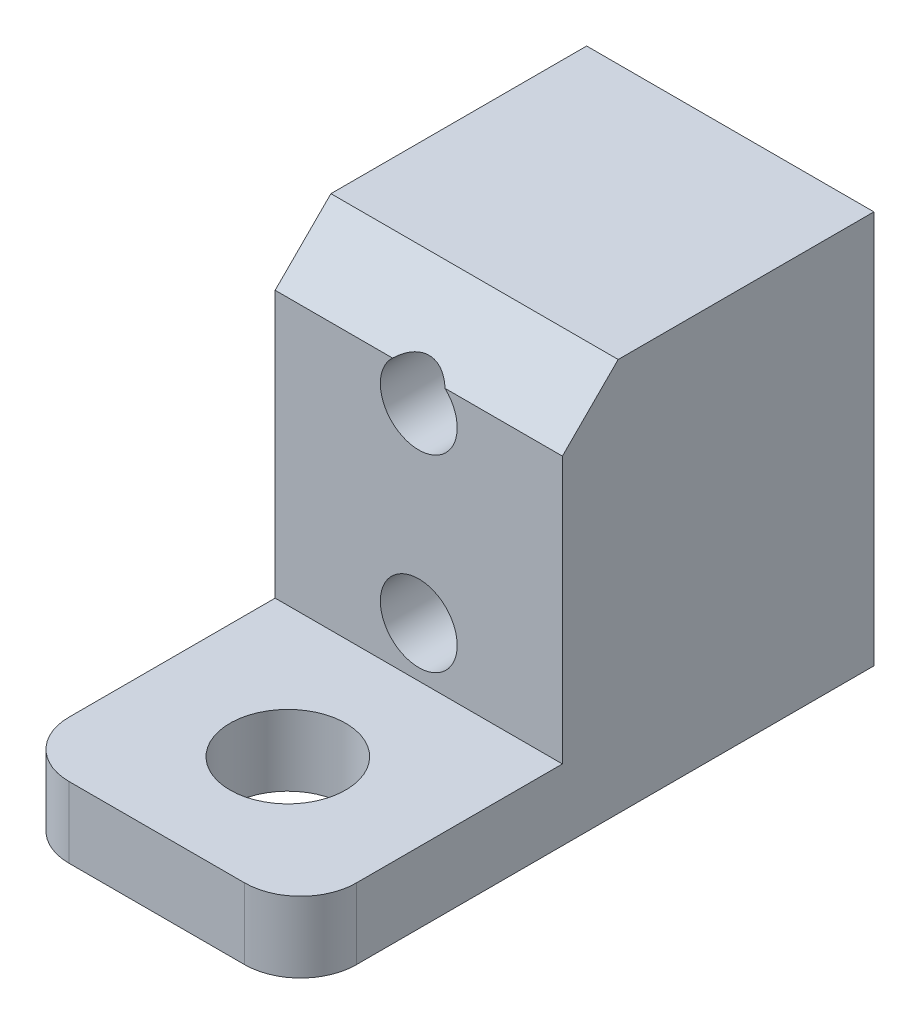
SolidWorks part; units mm, degrees
ref_plane "Front Plane" through (0, 0, 0) normal (0, 0, 1) x (1, 0, 0)
ref_plane "Top Plane" through (0, 0, 0) normal (0, 1, 0) x (1, 0, 0)
ref_plane "Right Plane" through (0, 0, 0) normal (1, 0, 0) x (0, 0, -1)
sketch "Sketch1" plane through (0, 0, 0) normal (0, 0, 1) x (1, 0, 0)
  line L1 (-6.5405, -8.9535) -> (6.5405, -8.9535)
  line L2 (-6.5405, -8.9535) -> (-6.5405, 8.9535)
  line L3 (-6.5405, 8.9535) -> (6.5405, 8.9535)
  line L4 (6.5405, -8.9535) -> (6.5405, 8.9535)
  line L5 (-6.5405, -8.9535) -> (6.5405, 8.9535) construction
  line L6 (-6.5405, 8.9535) -> (6.5405, -8.9535) construction
  point P0 (0, 0)
  dimension "D1" = 17.907
  dimension "D2" = 13.081
extrude "Boss-Extrude1" add sketch "Sketch1" along normal blind 14.1859
sketch "Sketch2" plane through (0, 0, 14.1859) normal (0, 0, 1) x (1, 0, 0)
  line L0 (6.5405, -8.9535) -> (6.5405, 8.9535) construction
  line L1 (-6.5405, -8.9535) -> (6.5405, -8.9535)
  line L2 (-6.5405, -8.9535) -> (-6.5405, -5.7277)
  line L3 (-6.5405, -5.7277) -> (6.5405, -5.7277)
  line L4 (6.5405, -8.9535) -> (6.5405, -5.7277)
  dimension "D1" = 3.2258
extrude "Boss-Extrude2" add sketch "Sketch2" along normal blind 11.9253
chamfer "Chamfer1" distance 2.54 angle 45 1 edges at (0, 8.9535, 14.1859)
fillet "Fillet1" radius 2.54 2 edges at (6.5405, -7.3406, 26.1112) (-6.5405, -7.3406, 26.1112)
sketch "Sketch3" plane through (0, -5.7277, 0) normal (0, 1, 0) x (1, 0, 0)
  line L0 (0, -26.1112) -> (0, -14.1859) construction
  line L2 (4.0005, -26.1112) -> (-4.0005, -26.1112) construction
  line L4 (6.5405, -14.1859) -> (-6.5405, -14.1859) construction
  line L5 (0, -20.1486) -> (-6.5405, -20.1486) construction
  line L6 (-6.5405, -23.5712) -> (-6.5405, -14.1859) construction
  circle A0 centre (0, -20.1486) radius 2.6353
  dimension "D1" = 5.2705
extrude "Cut-Extrude1" cut sketch "Sketch3" against normal up to surface (3.2258 mm away) up to face at (0, -8.9535, 16.7362)
sketch "Sketch4" plane through (0, 0, 0) normal (0, 0, -1) x (-1, 0, 0)
  line L0 (0, 5.1334) -> (0, 8.9535) construction
  line L1 (0, 5.1334) -> (0, -3.4466) construction
  line L3 (-6.5405, 8.9535) -> (6.5405, 8.9535) construction
  line L4 (0, 5.1334) -> (6.5405, 5.1334) construction
  line L5 (6.5405, 8.9535) -> (6.5405, -8.9535) construction
  circle A0 centre (0, 5.1334) radius 1.75
  circle A1 centre (0, -3.4466) radius 1.75
  dimension "D3" = 3.5
  dimension "D1" = 8.58
extrude "Cut-Extrude2" cut sketch "Sketch4" against normal through all
